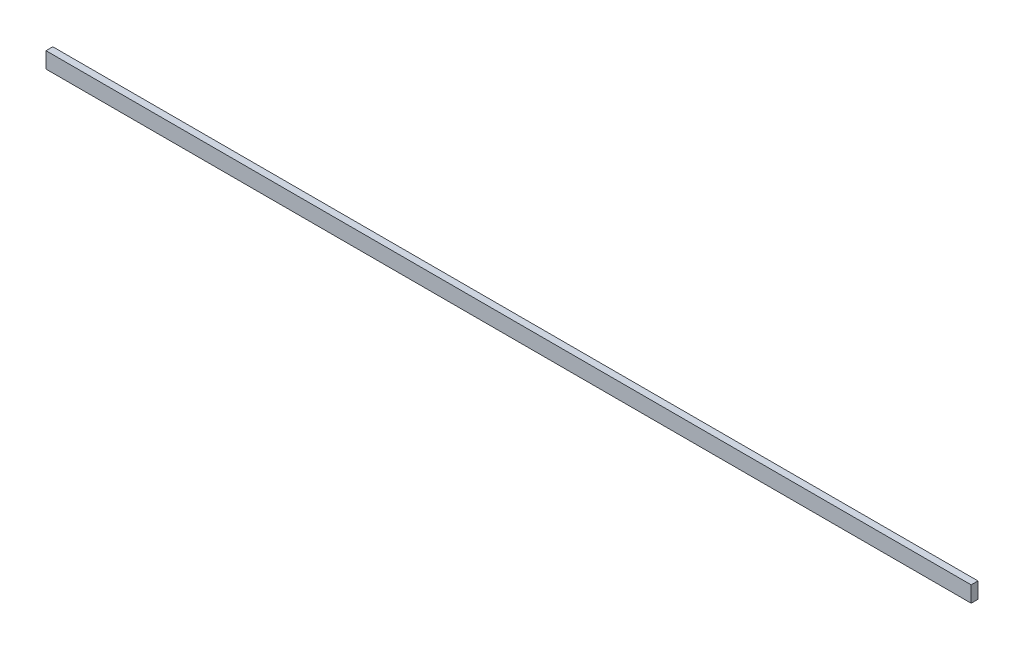
SolidWorks part; units mm, degrees
ref_plane "Front Plane" through (0, 0, 0) normal (1, 0, 0) x (0, 1, 0)
ref_plane "Top Plane" through (0, 0, 0) normal (0, 0, 1) x (0, 1, 0)
ref_plane "Right Plane" through (0, 0, 0) normal (0, 1, 0) x (-1, 0, 0)
sketch "Sketch1" plane through (0, 0, 0) normal (1, 0, 0) x (0, 1, 0)
  line L1 (-44.45, -19.05) -> (44.45, -19.05)
  line L2 (-44.45, -19.05) -> (-44.45, 19.05)
  line L3 (-44.45, 19.05) -> (44.45, 19.05)
  line L4 (44.45, -19.05) -> (44.45, 19.05)
  line L5 (-44.45, -19.05) -> (44.45, 19.05) construction
  line L6 (-44.45, 19.05) -> (44.45, -19.05) construction
  point P0 (0, 0)
  dimension "D1" = 38.1
  dimension "D2" = 88.9
extrude "Boss-Extrude1" add sketch "Sketch1" along normal blind 5161.28
